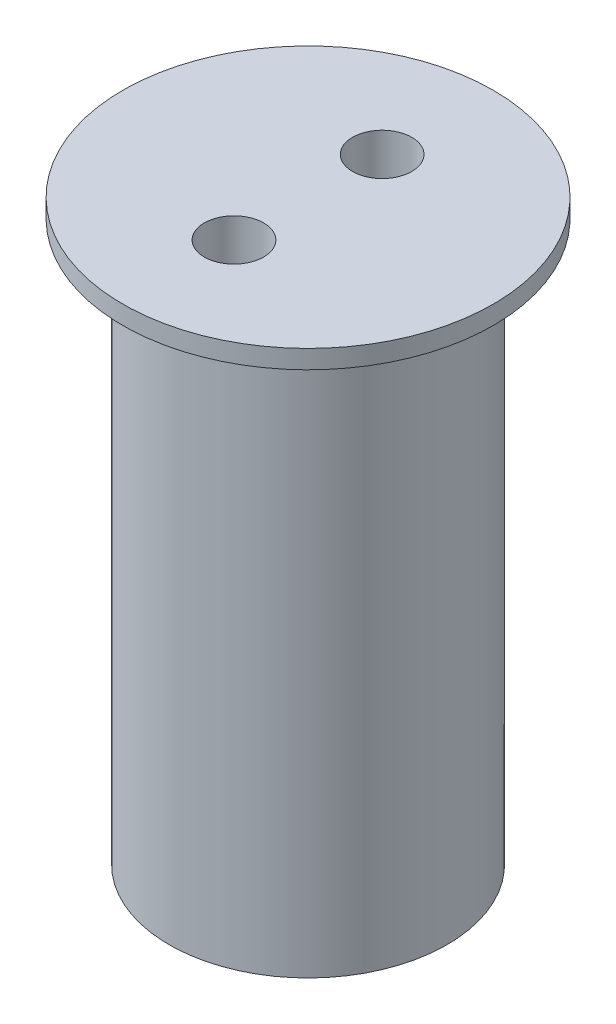
SolidWorks part; units mm, degrees
ref_plane "前视基准面" through (0, 0, 0) normal (0, 0, 1) x (1, 0, 0)
ref_plane "上视基准面" through (0, 0, 0) normal (0, 1, 0) x (1, 0, 0)
ref_plane "右视基准面" through (0, 0, 0) normal (1, 0, 0) x (0, 0, -1)
other "Configuration Table"
sketch "草图1" plane through (0, 0, 0) normal (0, 0, 1) x (1, 0, 0)
  line L0 (0, 14.9695) -> (10, 14.9695)
  line L1 (10, 14.9695) -> (10, 13.9695)
  line L2 (10, 13.9695) -> (7.5, 13.9695)
  line L3 (7.5, 13.9695) -> (7.5, -16.2305)
  line L4 (7.5, -16.2305) -> (0, -16.2305)
  line L5 (0, -16.2305) -> (0, 14.9695)
  dimension "D1" = 7.5
  dimension "D2" = 31.2
  dimension "D3" = 10
  dimension "D4" = 1
revolve "旋转1" add sketch "草图1" angle 360 about L5
sketch "草图2" plane through (0, -16.2305, 0) normal (0, -1, 0) x (1, 0, 0)
  circle A0 centre (0, 0) radius 4 construction
  circle A1 centre (0, 4) radius 1.6
  circle A2 centre (0, -4) radius 1.6
  point P9 (0, 0)
  dimension "D1" = 3.2
  dimension "D2" = 8
  dimension "D3" = 2
extrude "切除-拉伸1" cut sketch "草图2" against normal blind 42
